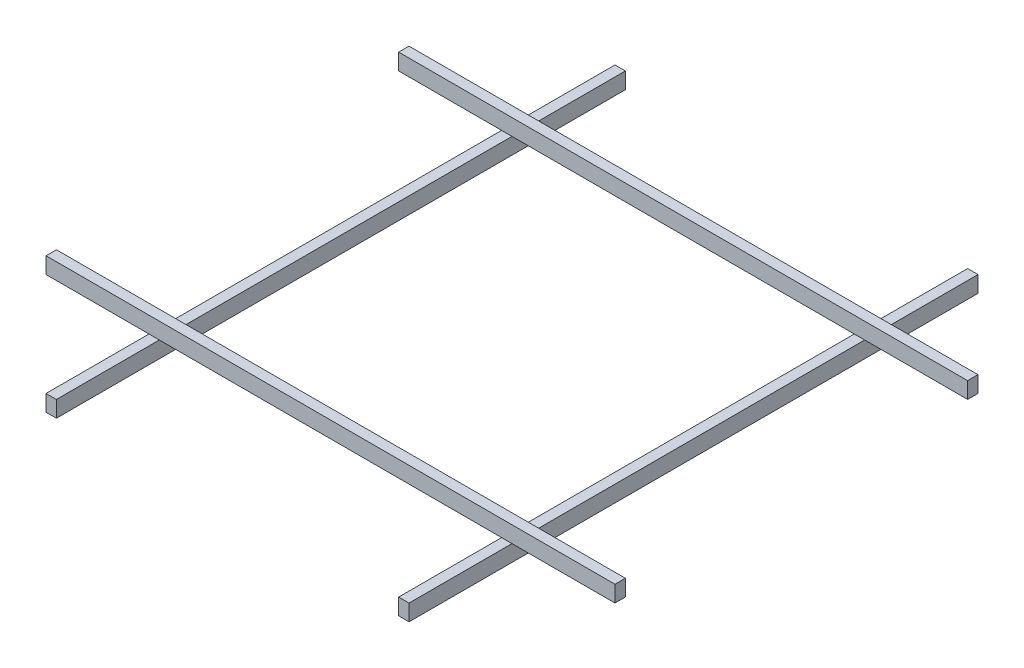
SolidWorks part; units mm, degrees
material "Doug Fir"
ref_plane "Front Plane" through (0, 0, 0) normal (0, 0, 1) x (1, 0, 0)
ref_plane "Top Plane" through (0, 0, 0) normal (0, 1, 0) x (1, 0, 0)
ref_plane "Right Plane" through (0, 0, 0) normal (1, 0, 0) x (0, 0, -1)
sketch "Lower Level" plane through (0, 0, 0) normal (0, 1, 0) x (1, 0, 0)
  line L0 (622.3, 0) -> (622.3, 4876.8)
  line L1 (3644.9, 0) -> (3644.9, 4876.8)
  line L2 (622.3, 2438.4) -> (3644.9, 2438.4) construction
  point P7 (2133.6, 2438.4)
  dimension "D1" = 4876.8
  dimension "D2" = 1511.3
ref_plane "Plane2" through (0, 139.7, 0) normal (0, 1, 0) x (1, 0, 0)
sketch "Sketch12" plane through (0, 139.7, 0) normal (0, 1, 0) x (1, 0, 0)
  line L0 (-304.8, 3949.7) -> (4572, 3949.7)
  line L1 (4572, 927.1) -> (-304.8, 927.1)
  line L2 (2133.6, 3949.7) -> (2133.6, 927.1) construction
  point P0 (2133.6, 2438.4)
  point P6 (2133.6, 927.1)
  point P7 (2133.6, 3949.7)
  point P10 (2133.6, 2438.4)
  dimension "D1" = 4876.8
  dimension "D2" = 1511.3
other "Profiles 4X6(1)"
ref_plane "Plane1" through (622.3, 0, 0) normal (0, 0, -1) x (-1, 0, 0)
sketch "Sketch1" plane through (622.3, 0, 0) normal (0, 0, -1) x (-1, 0, 0)
  line L1 (-44.45, 69.85) -> (44.45, 69.85)
  line L2 (-44.45, 69.85) -> (-44.45, -69.85)
  line L3 (-44.45, -69.85) -> (44.45, -69.85)
  line L4 (44.45, 69.85) -> (44.45, -69.85)
  line L5 (-44.45, 69.85) -> (44.45, -69.85) construction
  line L6 (-44.45, -69.85) -> (44.45, 69.85) construction
  point P0 (0, 0)
  point P6 (0, 69.85)
  point P7 (0, -69.85)
  point P8 (44.45, 0)
  point P9 (-44.45, 0)
  point P10 (0, 0)
  dimension "D1" = 88.9
  dimension "D2" = 139.7
sketch3d "3DSketch2"
  line L0 (2133.6, 139.7, -2438.4) -> (2133.6, 0, -2438.4)
  line L1 (622.3, 0, -2438.4) -> (3644.9, 0, -2438.4) construction
equation "\"Width\" = 59.5"
equation "\"Length\"=192"
equation "\"D1@Lower Level\"=\"Length\""
equation "\"D2@Lower Level\"=\"Width\""
equation "\"D1@Sketch12\"=\"Length\""
equation "\"D2@Sketch12\"=\"Width\""
